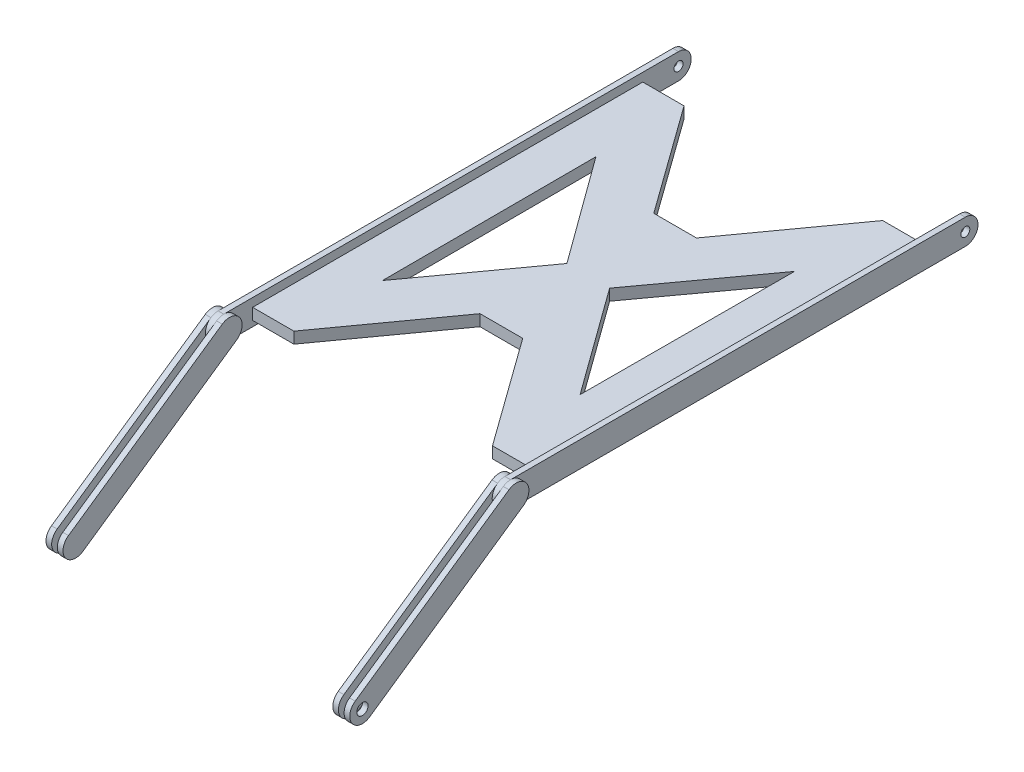
SolidWorks part; units mm, degrees
ref_plane "Front Plane" through (0, 0, 0) normal (0, 0, 1) x (1, 0, 0)
ref_plane "Top Plane" through (0, 0, 0) normal (0, 1, 0) x (1, 0, 0)
ref_plane "Right Plane" through (0, 0, 0) normal (1, 0, 0) x (0, 0, -1)
sketch "Sketch3" plane through (0, 0, 0) normal (0, 1, 0) x (1, 0, 0)
  line L0 (-78.7795, 0) -> (78.7795, 0) construction
  line L1 (-78.7795, -109.3484) -> (78.7795, -109.3484)
  line L2 (-78.7795, -109.3484) -> (-78.7795, 109.3484)
  line L3 (-78.7795, 109.3484) -> (78.7795, 109.3484)
  line L4 (78.7795, -109.3484) -> (78.7795, 109.3484)
  line L5 (-78.7795, -109.3484) -> (78.7795, 109.3484) construction
  line L6 (-78.7795, 109.3484) -> (78.7795, -109.3484) construction
  line L7 (11.9713, 48.7033) -> (55.6627, 109.3484)
  line L8 (-11.9713, 48.7033) -> (11.9713, 48.7033)
  line L9 (-55.6627, -109.3484) -> (-11.9713, -48.7033)
  line L10 (-11.9713, -48.7033) -> (11.9713, -48.7033)
  line L11 (11.9713, -48.7033) -> (55.6627, -109.3484)
  line L16 (-55.6627, 109.3484) -> (-11.9713, 48.7033)
  line L17 (-55.3786, -59.9545) -> (-55.6627, 59.9545)
  line L18 (-55.6627, 59.9545) -> (-11.9713, 0)
  line L19 (-11.9713, 0) -> (-55.3786, -59.9545)
  line L20 (0, -109.3484) -> (0, 109.3484) construction
  line L21 (55.6627, 59.9545) -> (11.9713, 0)
  line L22 (55.3786, -59.9545) -> (55.6627, 59.9545)
  line L23 (11.9713, 0) -> (55.3786, -59.9545)
  point P0 (0, 0)
  point P7 (0, 109.3484)
  point P8 (78.7795, 0)
  point P18 (0, -109.3484)
  point P20 (0, -48.7033)
  point P22 (-55.5207, 0)
extrude "Boss-Extrude1" add sketch "Sketch3" along normal blind 6.35 contours L16 L3 L2 L1 L9 L10 L11 L4 L7 L8 L23 L21 L22 L18 L19 L17
sketch "Sketch4" plane through (78.7795, 0, 0) normal (1, 0, 0) x (0, 0, -1)
  line L0 (-125.5088, 3.9969) -> (129.3847, 3.9969) construction
  line L3 (-125.5088, 11.1139) -> (129.3847, 11.1139)
  line L4 (-125.5088, -3.1201) -> (129.3847, -3.1201)
  arc A0 (-125.5088, 11.1139) -> (-125.5088, -3.1201) centre (-125.5088, 3.9969) ccw
  arc A1 (129.3847, -3.1201) -> (129.3847, 11.1139) centre (129.3847, 3.9969) ccw
  point P2 (-125.5088, 3.175)
  point P3 (129.3847, 3.9969)
  point P6 (1.9379, 3.9969)
  point P11 (-109.3484, 3.175)
extrude "Boss-Extrude2" add sketch "Sketch4" along normal blind 3.175
mirror "Mirror1" about plane through (0, 0, 0) normal (1, 0, 0) of "Boss-Extrude2"
sketch "Sketch5" plane through (81.9545, 0, 0) normal (1, 0, 0) x (0, 0, -1)
  line L0 (-125.5088, 3.9969) -> (-211.7066, -55.5154) construction
  line L1 (-121.4681, -1.8557) -> (-207.6659, -61.368)
  line L2 (-129.5496, 9.8495) -> (-215.7474, -49.6628)
  arc A0 (-121.4681, -1.8557) -> (-129.5496, 9.8495) centre (-125.5088, 3.9969) ccw
  arc A1 (-215.7474, -49.6628) -> (-207.6659, -61.368) centre (-211.7066, -55.5154) ccw
  point P3 (-168.6077, -25.7593)
  point P8 (-121.8258, -3.1201)
  point P9 (-122.5715, -3.1201)
  point P10 (-243.2944, -56.7218)
  point P11 (-236.3574, -74.5289)
  point P12 (-131.3102, 11.1139)
  point P13 (-211.7066, -55.5154)
extrude "Boss-Extrude3" add sketch "Sketch5" along normal blind 3.175
sketch "Sketch6" plane through (85.1295, 0, 0) normal (1, 0, 0) x (0, 0, -1)
  circle A0 centre (-211.7066, -55.5154) radius 3.175
  dimension "D1" = 6.35
extrude "Cut-Extrude1" cut sketch "Sketch6" against normal through all
ref_plane "Plane4" through (80.367, 0, 0) normal (1, 0, 0) x (0, 0, -1)
ref_plane "Plane5" through (-80.367, 0, 0) normal (1, 0, 0) x (0, 0, -1)
mirror "Mirror3" about plane through (80.367, 0, 0) normal (1, 0, 0) of "Boss-Extrude3"
mirror "Mirror4" about plane through (0, 0, 0) normal (1, 0, 0) of "Mirror3", "Boss-Extrude3"
sketch "Sketch7" plane through (81.9545, 0, 0) normal (1, 0, 0) x (0, 0, -1)
  circle A0 centre (129.3847, 3.9969) radius 2.54
extrude "Cut-Extrude2" cut sketch "Sketch7" against normal through all
